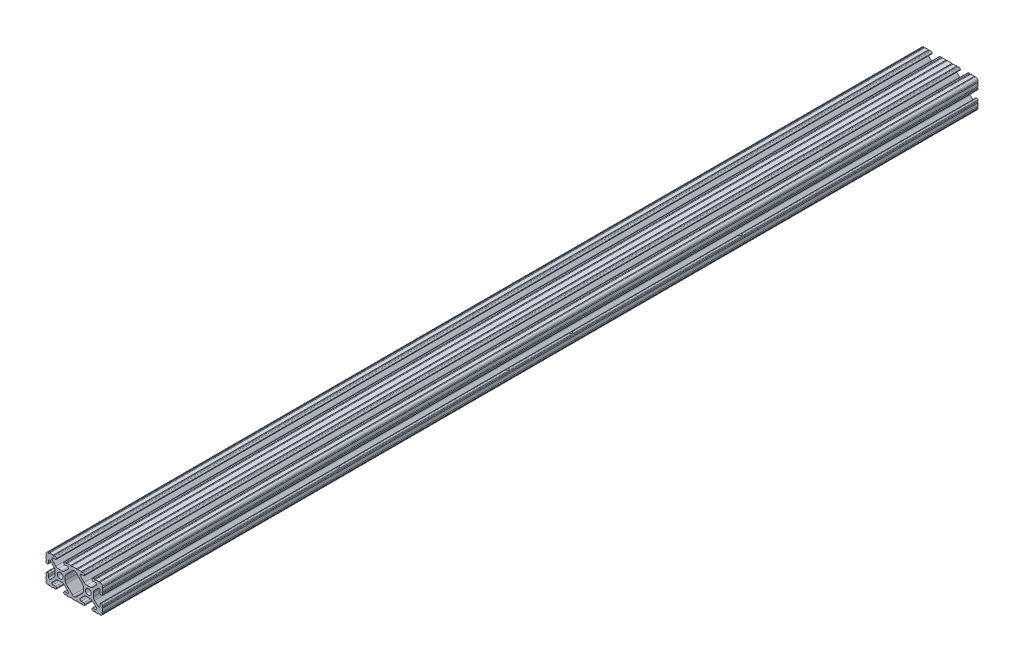
SolidWorks part; units mm, degrees
ref_plane "Front Plane" through (0, 0, 0) normal (0, 0, 1) x (1, 0, 0)
ref_plane "Top Plane" through (0, 0, 0) normal (0, 1, 0) x (1, 0, 0)
ref_plane "Right Plane" through (0, 0, 0) normal (1, 0, 0) x (0, 0, -1)
sketch "Sketch1" plane through (0, 0, 0) normal (0, 0, 1) x (1, 0, 0)
  line L0 (-7.2595, -3.8694) -> (-1.5457, -9.5728)
  line L1 (-8.1915, 1.6223) -> (-8.1915, -1.6223)
  line L2 (-1.504, 9.5765) -> (-7.252, 3.8768)
  line L3 (0.5515, 10.033) -> (-0.3952, 10.033)
  line L4 (7.2829, 3.8459) -> (1.6756, 9.5611)
  line L5 (8.1915, -1.6223) -> (8.1915, 1.6223)
  line L6 (1.5457, -9.5728) -> (7.2595, -3.8694)
  line L7 (-0.4332, -10.033) -> (0.4332, -10.033)
  line L8 (18.0171, 12.7) -> (16.9875, 12.7)
  line L9 (15.9385, 11.651) -> (15.9385, 11.5392)
  line L10 (16.9875, 10.4902) -> (19.1164, 10.4902)
  line L11 (19.8441, 8.7652) -> (16.619, 5.4551)
  line L12 (14.3449, 4.4958) -> (11.0833, 4.4958)
  line L13 (8.817, 5.4472) -> (5.5642, 8.7627)
  line L14 (6.2894, 10.4902) -> (8.4125, 10.4902)
  line L15 (9.4615, 11.5392) -> (9.4615, 11.651)
  line L16 (8.4125, 12.7) -> (7.3829, 12.7)
  line L17 (6.3669, 12.7) -> (3.1496, 12.7)
  line L18 (2.1336, 12.7) -> (-2.1336, 12.7)
  line L19 (-3.1496, 12.7) -> (-6.3669, 12.7)
  line L20 (-7.3829, 12.7) -> (-8.4125, 12.7)
  line L21 (-9.4615, 11.651) -> (-9.4615, 11.5392)
  line L22 (-8.4125, 10.4902) -> (-6.2836, 10.4902)
  line L23 (-5.5326, 8.6661) -> (-8.81, 5.4163)
  line L24 (-11.0455, 4.4958) -> (-14.3545, 4.4958)
  line L25 (-16.59, 5.4163) -> (-19.8674, 8.6661)
  line L26 (-19.1164, 10.4902) -> (-16.9875, 10.4902)
  line L27 (-15.9385, 11.5392) -> (-15.9385, 11.651)
  line L28 (-16.9875, 12.7) -> (-18.0171, 12.7)
  line L29 (-19.0331, 12.7) -> (-22.2504, 12.7)
  line L30 (-25.4, 9.5504) -> (-25.4, 6.3331)
  line L31 (-25.4, 5.3171) -> (-25.4, 4.2375)
  line L32 (-24.401, 3.2385) -> (-24.2392, 3.2385)
  line L33 (-23.1902, 4.2875) -> (-23.1902, 6.3347)
  line L34 (-21.434, 7.0665) -> (-18.148, 3.8082)
  line L35 (-17.2085, 1.5536) -> (-17.2085, -1.6952)
  line L36 (-18.1405, -3.9423) -> (-21.4316, -7.2274)
  line L37 (-23.1902, -6.498) -> (-23.1902, -4.2875)
  line L38 (-24.2392, -3.2385) -> (-24.351, -3.2385)
  line L39 (-25.4, -4.2875) -> (-25.4, -5.3171)
  line L40 (-25.4, -6.3331) -> (-25.4, -9.5504)
  line L41 (-22.2504, -12.7) -> (-19.0331, -12.7)
  line L42 (-18.0171, -12.7) -> (-16.9875, -12.7)
  line L43 (-15.9384, -11.651) -> (-15.9384, -11.5392)
  line L44 (-16.9875, -10.4902) -> (-19.1164, -10.4902)
  line L45 (-19.8341, -8.7551) -> (-16.4966, -5.4237)
  line L46 (-14.2536, -4.4958) -> (-11.1464, -4.4958)
  line L47 (-8.9034, -5.4237) -> (-5.5659, -8.7551)
  line L48 (-6.2836, -10.4902) -> (-8.4125, -10.4902)
  line L49 (-9.4616, -11.5392) -> (-9.4616, -11.651)
  line L50 (-8.4125, -12.7) -> (-7.3829, -12.7)
  line L51 (-6.3669, -12.7) -> (-3.1496, -12.7)
  line L52 (-2.1336, -12.7) -> (2.1336, -12.7)
  line L53 (3.1496, -12.7) -> (6.3669, -12.7)
  line L54 (7.3829, -12.7) -> (8.4125, -12.7)
  line L55 (9.4616, -11.651) -> (9.4616, -11.5392)
  line L56 (8.4125, -10.4902) -> (6.2894, -10.4902)
  line L57 (5.4807, -8.5353) -> (8.5979, -5.4237)
  line L58 (10.8409, -4.4958) -> (14.1026, -4.4958)
  line L59 (16.1879, -5.2766) -> (19.8682, -8.4822)
  line L60 (19.1164, -10.4902) -> (16.9875, -10.4902)
  line L61 (15.9384, -11.5392) -> (15.9384, -11.651)
  line L62 (16.9875, -12.7) -> (18.0171, -12.7)
  line L63 (19.0331, -12.7) -> (22.2504, -12.7)
  line L64 (25.4, -9.5504) -> (25.4, -6.3331)
  line L65 (25.4, -5.3171) -> (25.4, -4.2375)
  line L66 (24.401, -3.2385) -> (24.1892, -3.2385)
  line L67 (23.1902, -4.2375) -> (23.1902, -6.1559)
  line L68 (21.584, -6.8869) -> (18.2982, -4.025)
  line L69 (17.2085, -1.6308) -> (17.2085, 1.6308)
  line L70 (18.1094, 3.8465) -> (21.5263, 7.3534)
  line L71 (23.1902, 6.6769) -> (23.1902, 4.2375)
  line L72 (24.1892, 3.2385) -> (24.401, 3.2385)
  line L73 (25.4, 4.2375) -> (25.4, 5.3171)
  line L74 (25.4, 6.3332) -> (25.4, 9.5504)
  line L75 (22.2504, 12.7) -> (19.0331, 12.7)
  circle A0 centre (-12.7, 0) radius 2.6035
  circle A1 centre (12.7, 0) radius 2.6035
  arc A2 (-1.5457, -9.5728) -> (-0.4332, -10.033) centre (-0.4332, -8.4582) ccw
  arc A3 (-8.1915, -1.6223) -> (-7.2595, -3.8694) centre (-5.0165, -1.6223) ccw
  arc A4 (-7.252, 3.8768) -> (-8.1915, 1.6223) centre (-5.0165, 1.6223) ccw
  arc A5 (-0.3952, 10.033) -> (-1.504, 9.5765) centre (-0.3952, 8.4582) ccw
  arc A6 (1.6756, 9.5611) -> (0.5515, 10.033) centre (0.5515, 8.4582) ccw
  arc A7 (8.1915, 1.6223) -> (7.2829, 3.8459) centre (5.0165, 1.6223) ccw
  arc A8 (7.2595, -3.8694) -> (8.1915, -1.6223) centre (5.0165, -1.6223) ccw
  arc A9 (0.4332, -10.033) -> (1.5457, -9.5728) centre (0.4332, -8.4582) ccw
  arc A10 (18.0171, 12.7) -> (19.0331, 12.7) centre (18.5251, 12.7) ccw
  arc A11 (16.9875, 12.7) -> (15.9385, 11.651) centre (16.9875, 11.651) ccw
  arc A12 (15.9385, 11.5392) -> (16.9875, 10.4902) centre (16.9875, 11.5392) ccw
  arc A13 (19.8441, 8.7652) -> (19.1164, 10.4902) centre (19.1164, 9.4742) ccw
  arc A14 (14.3449, 4.4958) -> (16.619, 5.4551) centre (14.3449, 7.6708) ccw
  arc A15 (8.817, 5.4472) -> (11.0833, 4.4958) centre (11.0833, 7.6708) ccw
  arc A16 (6.2894, 10.4902) -> (5.5642, 8.7627) centre (6.2894, 9.4742) ccw
  arc A17 (8.4125, 10.4902) -> (9.4615, 11.5392) centre (8.4125, 11.5392) ccw
  arc A18 (9.4615, 11.651) -> (8.4125, 12.7) centre (8.4125, 11.651) ccw
  arc A19 (6.3669, 12.7) -> (7.3829, 12.7) centre (6.8749, 12.7) ccw
  arc A20 (2.1336, 12.7) -> (3.1496, 12.7) centre (2.6416, 12.7) ccw
  arc A21 (-3.1496, 12.7) -> (-2.1336, 12.7) centre (-2.6416, 12.7) ccw
  arc A22 (-7.3829, 12.7) -> (-6.3669, 12.7) centre (-6.8749, 12.7) ccw
  arc A23 (-8.4125, 12.7) -> (-9.4615, 11.651) centre (-8.4125, 11.651) ccw
  arc A24 (-9.4615, 11.5392) -> (-8.4125, 10.4902) centre (-8.4125, 11.5392) ccw
  arc A25 (-5.5326, 8.6661) -> (-6.2836, 10.4902) centre (-6.2836, 9.4235) ccw
  arc A26 (-11.0455, 4.4958) -> (-8.81, 5.4163) centre (-11.0455, 7.6708) ccw
  arc A27 (-16.59, 5.4163) -> (-14.3545, 4.4958) centre (-14.3545, 7.6708) ccw
  arc A28 (-19.1164, 10.4902) -> (-19.8674, 8.6661) centre (-19.1164, 9.4235) ccw
  arc A29 (-16.9875, 10.4902) -> (-15.9385, 11.5392) centre (-16.9875, 11.5392) ccw
  arc A30 (-15.9385, 11.651) -> (-16.9875, 12.7) centre (-16.9875, 11.651) ccw
  arc A31 (-19.0331, 12.7) -> (-18.0171, 12.7) centre (-18.5251, 12.7) ccw
  arc A32 (-23.2664, 12.6998) -> (-22.2504, 12.7) centre (-22.7584, 12.7) ccw
  arc A33 (-23.2664, 12.6998) -> (-25.3998, 10.5664) centre (-23.2918, 10.5918) ccw
  arc A34 (-25.4, 9.5504) -> (-25.3998, 10.5664) centre (-25.4, 10.0584) ccw
  arc A35 (-25.4, 5.3171) -> (-25.4, 6.3331) centre (-25.4, 5.8251) ccw
  arc A36 (-25.4, 4.2375) -> (-24.401, 3.2385) centre (-24.401, 4.2375) ccw
  arc A37 (-24.2392, 3.2385) -> (-23.1902, 4.2875) centre (-24.2392, 4.2875) ccw
  arc A38 (-21.434, 7.0665) -> (-23.1902, 6.3347) centre (-22.1596, 6.3347) ccw
  arc A39 (-17.2085, 1.5536) -> (-18.148, 3.8082) centre (-20.3835, 1.5536) ccw
  arc A40 (-18.1405, -3.9423) -> (-17.2085, -1.6952) centre (-20.3835, -1.6952) ccw
  arc A41 (-23.1902, -6.498) -> (-21.4316, -7.2274) centre (-22.1596, -6.498) ccw
  arc A42 (-23.1902, -4.2875) -> (-24.2392, -3.2385) centre (-24.2392, -4.2875) ccw
  arc A43 (-24.351, -3.2385) -> (-25.4, -4.2875) centre (-24.351, -4.2875) ccw
  arc A44 (-25.4, -6.3331) -> (-25.4, -5.3171) centre (-25.4, -5.8251) ccw
  arc A45 (-25.3998, -10.5664) -> (-25.4, -9.5504) centre (-25.4, -10.0584) ccw
  arc A46 (-25.3998, -10.5664) -> (-23.2664, -12.6998) centre (-23.2918, -10.5918) ccw
  arc A47 (-22.2504, -12.7) -> (-23.2664, -12.6998) centre (-22.7584, -12.7) ccw
  arc A48 (-18.0171, -12.7) -> (-19.0331, -12.7) centre (-18.5251, -12.7) ccw
  arc A49 (-16.9875, -12.7) -> (-15.9384, -11.651) centre (-16.9875, -11.651) ccw
  arc A50 (-15.9384, -11.5392) -> (-16.9875, -10.4902) centre (-16.9875, -11.5392) ccw
  arc A51 (-19.8341, -8.7551) -> (-19.1164, -10.4902) centre (-19.1164, -9.4742) ccw
  arc A52 (-14.2536, -4.4958) -> (-16.4966, -5.4237) centre (-14.2536, -7.6708) ccw
  arc A53 (-8.9034, -5.4237) -> (-11.1464, -4.4958) centre (-11.1464, -7.6708) ccw
  arc A54 (-6.2836, -10.4902) -> (-5.5659, -8.7551) centre (-6.2836, -9.4742) ccw
  arc A55 (-8.4125, -10.4902) -> (-9.4616, -11.5392) centre (-8.4125, -11.5392) ccw
  arc A56 (-9.4616, -11.651) -> (-8.4125, -12.7) centre (-8.4125, -11.651) ccw
  arc A57 (-6.3669, -12.7) -> (-7.3829, -12.7) centre (-6.8749, -12.7) ccw
  arc A58 (-2.1336, -12.7) -> (-3.1496, -12.7) centre (-2.6416, -12.7) ccw
  arc A59 (3.1496, -12.7) -> (2.1336, -12.7) centre (2.6416, -12.7) ccw
  arc A60 (7.3829, -12.7) -> (6.3669, -12.7) centre (6.8749, -12.7) ccw
  arc A61 (8.4125, -12.7) -> (9.4616, -11.651) centre (8.4125, -11.651) ccw
  arc A62 (9.4616, -11.5392) -> (8.4125, -10.4902) centre (8.4125, -11.5392) ccw
  arc A63 (5.4807, -8.5353) -> (6.2894, -10.4902) centre (6.2894, -9.3455) ccw
  arc A64 (10.8409, -4.4958) -> (8.5979, -5.4237) centre (10.8409, -7.6708) ccw
  arc A65 (16.1879, -5.2766) -> (14.1026, -4.4958) centre (14.1026, -7.6708) ccw
  arc A66 (19.1164, -10.4902) -> (19.8682, -8.4822) centre (19.1164, -9.3455) ccw
  arc A67 (16.9875, -10.4902) -> (15.9384, -11.5392) centre (16.9875, -11.5392) ccw
  arc A68 (15.9384, -11.651) -> (16.9875, -12.7) centre (16.9875, -11.651) ccw
  arc A69 (19.0331, -12.7) -> (18.0171, -12.7) centre (18.5251, -12.7) ccw
  arc A70 (23.2664, -12.6998) -> (22.2504, -12.7) centre (22.7584, -12.7) ccw
  arc A71 (23.2664, -12.6998) -> (25.3998, -10.5664) centre (23.2918, -10.5918) ccw
  arc A72 (25.4, -9.5504) -> (25.3998, -10.5664) centre (25.4, -10.0584) ccw
  arc A73 (25.4, -5.3171) -> (25.4, -6.3331) centre (25.4, -5.8251) ccw
  arc A74 (25.4, -4.2375) -> (24.401, -3.2385) centre (24.401, -4.2375) ccw
  arc A75 (24.1892, -3.2385) -> (23.1902, -4.2375) centre (24.1892, -4.2375) ccw
  arc A76 (21.584, -6.8869) -> (23.1902, -6.1559) centre (22.2207, -6.1559) ccw
  arc A77 (17.2085, -1.6308) -> (18.2982, -4.025) centre (20.3835, -1.6308) ccw
  arc A78 (18.1094, 3.8465) -> (17.2085, 1.6308) centre (20.3835, 1.6308) ccw
  arc A79 (23.1902, 6.6769) -> (21.5263, 7.3534) centre (22.2207, 6.6769) ccw
  arc A80 (23.1902, 4.2375) -> (24.1892, 3.2385) centre (24.1892, 4.2375) ccw
  arc A81 (24.401, 3.2385) -> (25.4, 4.2375) centre (24.401, 4.2375) ccw
  arc A82 (25.4, 6.3332) -> (25.4, 5.3171) centre (25.4, 5.8251) ccw
  arc A83 (25.3998, 10.5664) -> (25.4, 9.5504) centre (25.4, 10.0584) ccw
  arc A84 (25.3998, 10.5664) -> (23.2664, 12.6998) centre (23.2918, 10.5918) ccw
  arc A85 (22.2504, 12.7) -> (23.2664, 12.6998) centre (22.7584, 12.7) ccw
  point P248 (0, 10.033)
extrude "Boss-Extrude1" add sketch "Sketch1" along normal mid plane 787.4
sketch "Sketch2" plane through (17.2085, 0, 0) normal (1, 0, 0) x (0, 0, -1)
  line L1 (393.7, -1.6308) -> (393.7, 1.6308) construction
  line L2 (0, 0) -> (0, 191.3427) construction
  circle A0 centre (28.57, 0) radius 3.5
  circle A1 centre (-28.57, 0) radius 3.5
  circle A2 centre (180.97, 0) radius 3.5
  circle A3 centre (-180.97, 0) radius 3.5
  dimension "D1" = 7
  dimension "D2" = 365.13
  dimension "D3" = 7
  dimension "D4" = 152.4
extrude "Cut-Extrude1" cut sketch "Sketch2" against normal through all both and the other way through all
